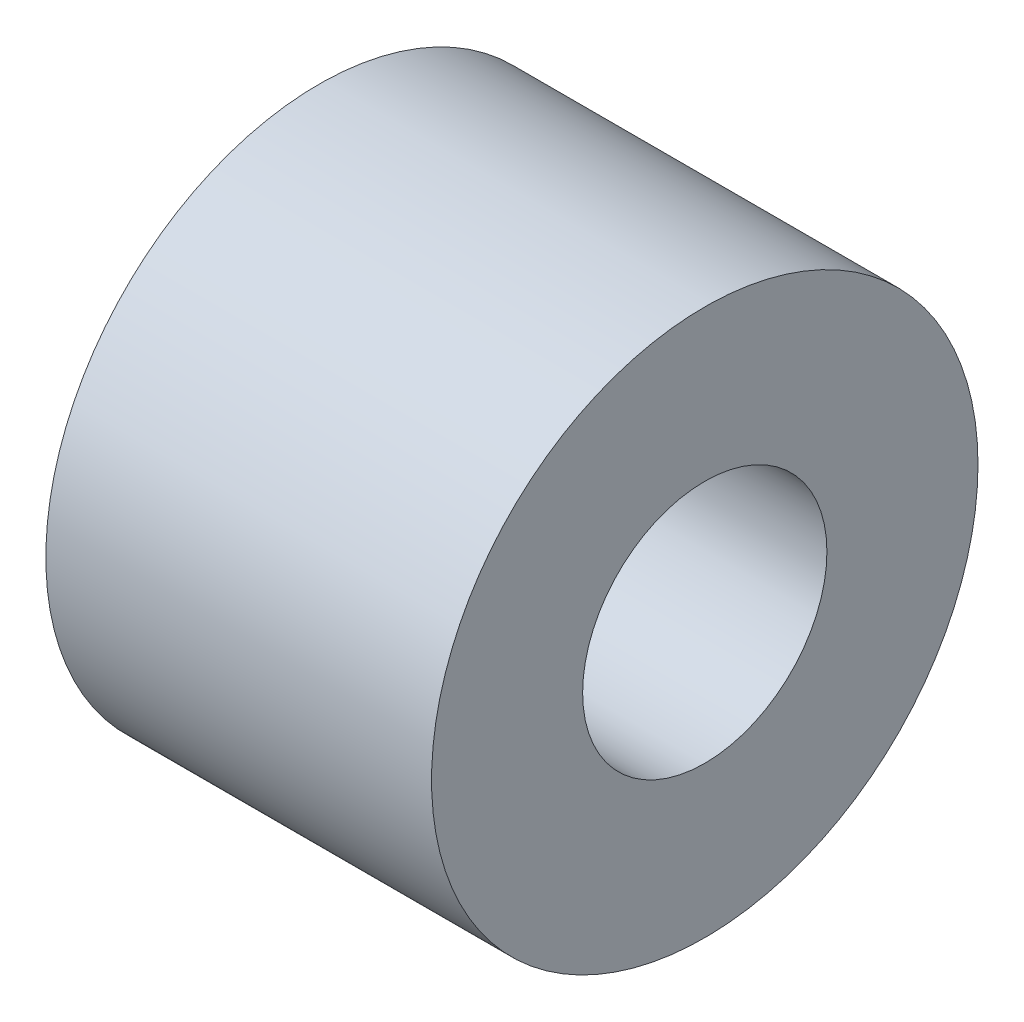
SolidWorks part; units mm, degrees
material "6061 Alloy"
ref_plane "Front Plane" through (0, 0, 0) normal (0, 0, 1) x (1, 0, 0)
ref_plane "Top Plane" through (0, 0, 0) normal (0, 1, 0) x (1, 0, 0)
ref_plane "Right Plane" through (0, 0, 0) normal (1, 0, 0) x (0, 0, -1)
sketch "Croquis1" plane through (0, 0, 0) normal (1, 0, 0) x (0, 0, -1)
  circle A0 centre (0, 0) radius 5.3975
  circle A1 centre (0, 0) radius 2.413
  dimension "D1" = 4.826
  dimension "D2" = 10.795
extrude "Saliente-Extruir1" add sketch "Croquis1" against normal blind 7.62
